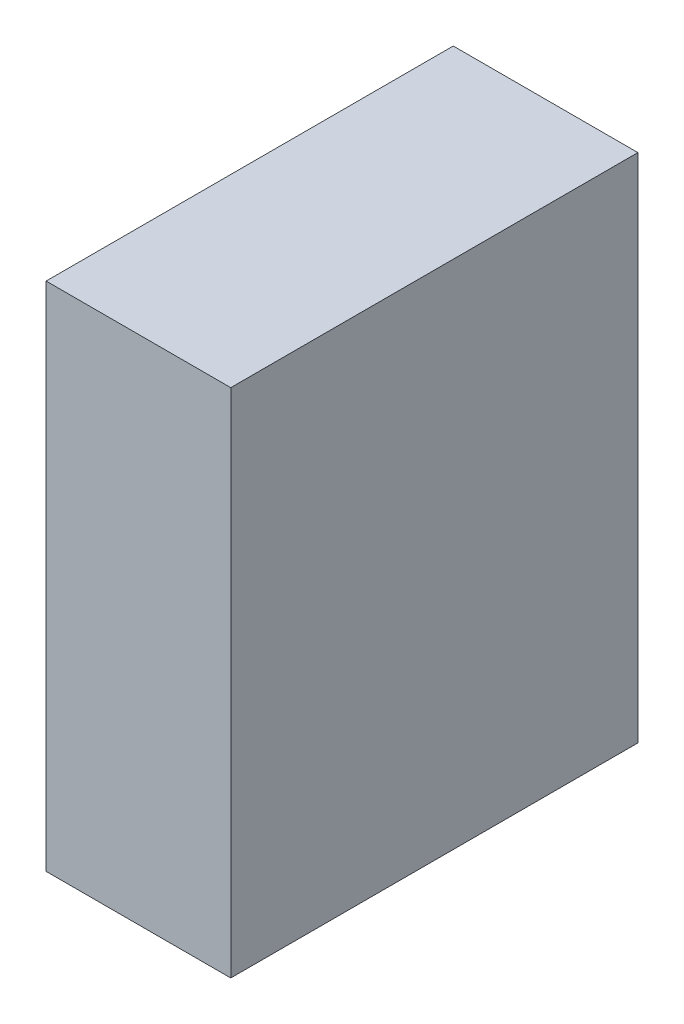
SolidWorks part; units mm, degrees
material "Plain Carbon Steel"
ref_plane "Front Plane" through (0, 0, 0) normal (0, 0, 1) x (1, 0, 0)
ref_plane "Top Plane" through (0, 0, 0) normal (0, 1, 0) x (1, 0, 0)
ref_plane "Right Plane" through (0, 0, 0) normal (1, 0, 0) x (0, 0, -1)
sketch "Sketch2" plane through (0, 0, 0) normal (1, 0, 0) x (0, 0, -1)
  line L1 (-414.8025, 57.7834) -> (-242.8025, 57.7834)
  line L2 (-414.8025, 57.7834) -> (-414.8025, -158.2166)
  line L3 (-414.8025, -158.2166) -> (-242.8025, -158.2166)
  line L4 (-242.8025, 57.7834) -> (-242.8025, -158.2166)
  dimension "D1" = 216
  dimension "D2" = 172
extrude "Boss-Extrude1" add sketch "Sketch2" along normal blind 78
